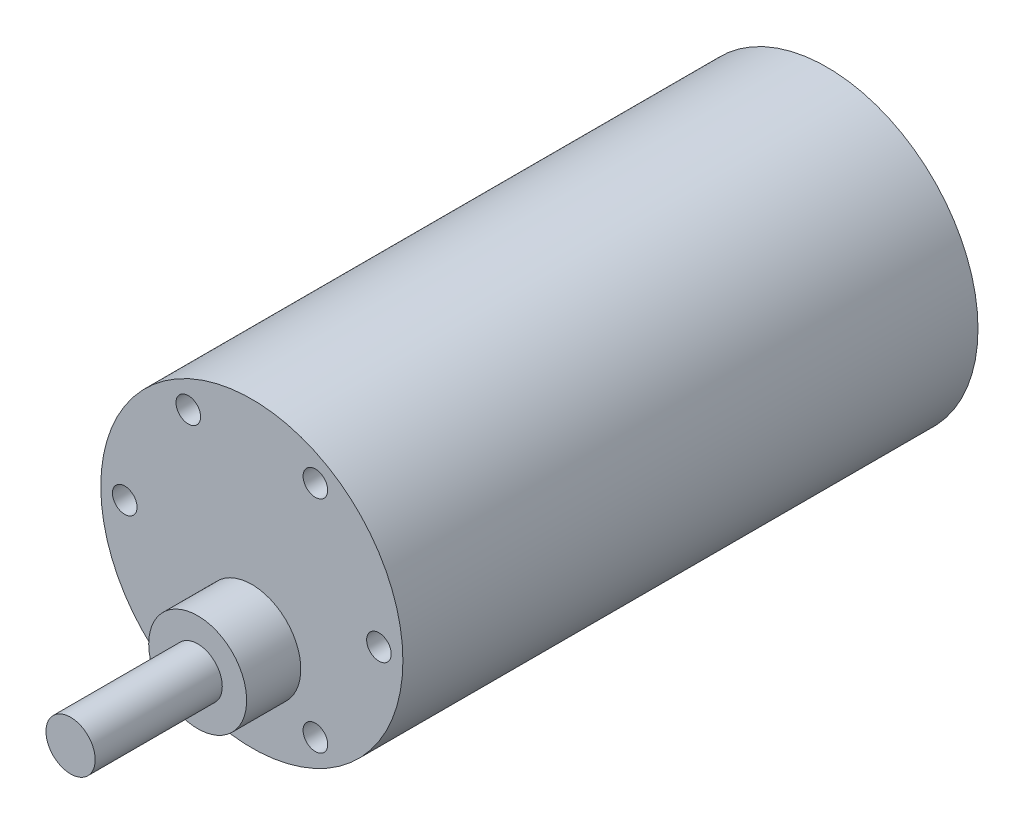
SolidWorks part; units mm, degrees
ref_plane "Front Plane" through (0, 0, 0) normal (0, 0, 1) x (1, 0, 0)
ref_plane "Top Plane" through (0, 0, 0) normal (0, 1, 0) x (1, 0, 0)
ref_plane "Right Plane" through (0, 0, 0) normal (1, 0, 0) x (0, 0, -1)
sketch "Sketch1" plane through (0, 0, 0) normal (0, 0, 1) x (1, 0, 0)
  circle A0 centre (0, 0) radius 18.415
  dimension "D1" = 36.83
extrude "Boss-Extrude1" add sketch "Sketch1" along normal blind 70.104
sketch "Sketch2" plane through (0, 0, 70.104) normal (0, 0, 1) x (1, 0, 0)
  line L0 (-18.415, 0) -> (18.415, 0) construction
  line L1 (0, 18.415) -> (0, -18.415) construction
  circle A0 centre (0, 0) radius 18.415 construction
  circle A1 centre (0, -7.112) radius 5.969
  dimension "D2" = 11.938
  dimension "D1" = 7.112
extrude "Boss-Extrude2" add sketch "Sketch2" along normal blind 6.604
sketch "Sketch3" plane through (0, 0, 76.708) normal (0, 0, 1) x (1, 0, 0)
  line L0 (0, -1.143) -> (0, -13.081) construction
  line L1 (-5.969, -7.112) -> (5.969, -7.112) construction
  circle A1 centre (0, -7.112) radius 5.969 construction
  circle A2 centre (0, -7.112) radius 5.969 construction
  circle A3 centre (0, -7.112) radius 3
  point P11 (-0.1842, -7.112)
  dimension "D1" = 6
extrude "Boss-Extrude3" add sketch "Sketch3" along normal blind 15.494
sketch "Sketch4" plane through (0, 0, 70.104) normal (0, 0, 1) x (1, 0, 0)
  line L0 (-18.415, 0) -> (18.415, 0) construction
  line L1 (-7.747, 13.4182) -> (0, 0) construction
  line L2 (0, 0) -> (7.747, 13.4182) construction
  line L3 (7.747, -13.4182) -> (0, 0) construction
  line L4 (0, 0) -> (-7.747, -13.4182) construction
  circle A0 centre (0, 0) radius 15.494 construction
  circle A1 centre (0, 0) radius 18.415 construction
  circle A2 centre (-15.494, 0) radius 1.5
  circle A3 centre (15.494, 0) radius 1.5
  circle A4 centre (7.747, 13.4182) radius 1.5
  circle A5 centre (-7.747, 13.4182) radius 1.5
  circle A6 centre (-7.747, -13.4182) radius 1.5
  circle A7 centre (7.747, -13.4182) radius 1.5
  point P8 (-15.494, 0)
  point P9 (15.494, 0)
  dimension "D1" = 30.988
  dimension "D2" = 3
  dimension "D3" = 60
  dimension "D4" = 60
  dimension "D5" = 60
  dimension "D6" = 60
extrude "Cut-Extrude1" cut sketch "Sketch4" against normal blind 25.4
